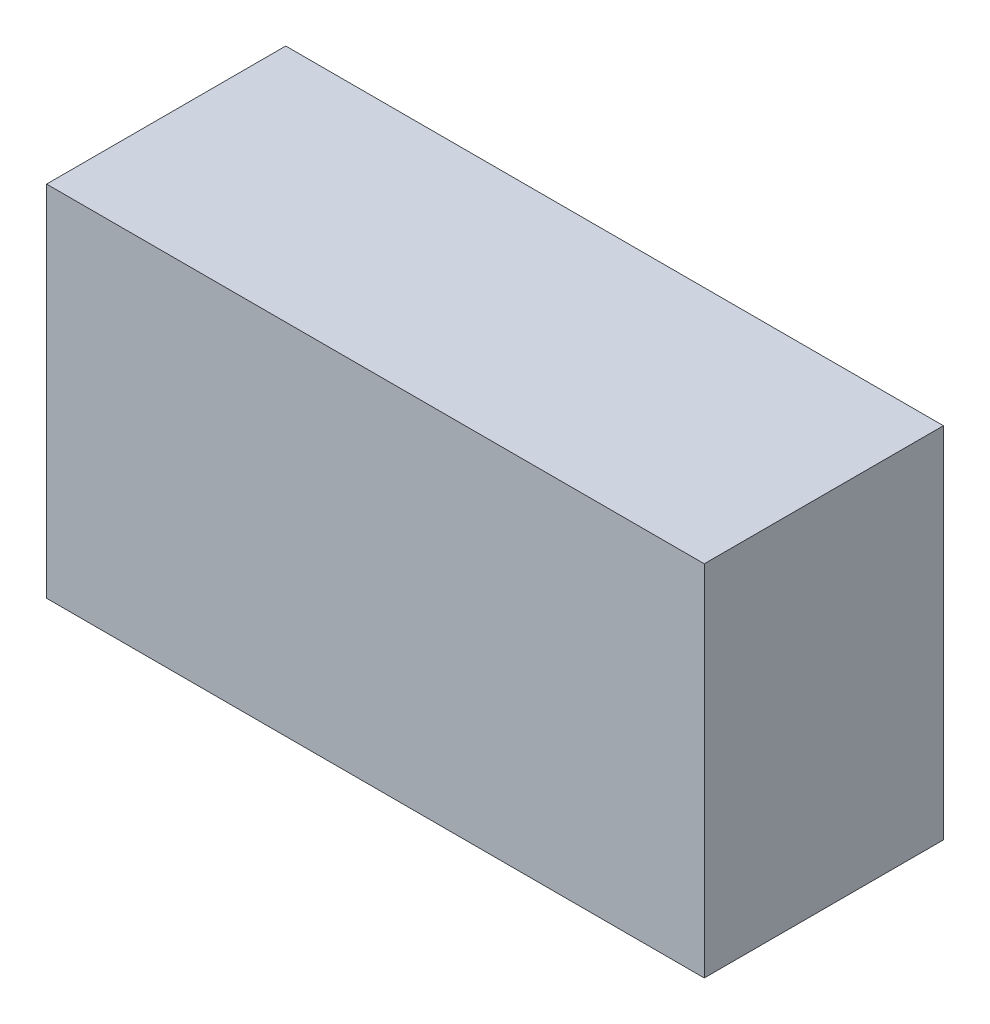
SolidWorks part; units mm, degrees
ref_plane "Спереди" through (0, 0, 0) normal (0, 0, 1) x (1, 0, 0)
ref_plane "Сверху" through (0, 0, 0) normal (0, 1, 0) x (1, 0, 0)
ref_plane "Справа" through (0, 0, 0) normal (1, 0, 0) x (0, 0, -1)
sketch "Эскиз1" plane through (0, 0, 0) normal (0, 0, 1) x (1, 0, 0)
  line L1 (0, 0) -> (33, 0)
  line L2 (0, 0) -> (0, 18)
  line L3 (0, 18) -> (33, 18)
  line L4 (33, 0) -> (33, 18)
  dimension "D1" = 33
  dimension "D2" = 18
extrude "Бобышка-Вытянуть1" add sketch "Эскиз1" along normal blind 12
sketch "Эскиз2" plane through (0, 0, 0) normal (-1, 0, 0) x (0, 0, 1)
  line L4 (2.7, 4.53) -> (3.3, 4.53)
  line L5 (4.58, 5.81) -> (4.58, 12.19)
  line L6 (3.3, 13.47) -> (2.7, 13.47)
  line L7 (1.42, 12.19) -> (1.42, 5.81)
  line L8 (12, 18) -> (0, 18) construction
  line L9 (4.58, 9) -> (1.42, 9) construction
  line L10 (0, 18) -> (0, 0) construction
  line L11 (3, 13.47) -> (3, 4.53) construction
  arc A4 (3.3, 4.53) -> (4.58, 5.81) centre (3.3, 5.81) ccw
  arc A5 (4.58, 12.19) -> (3.3, 13.47) centre (3.3, 12.19) ccw
  arc A6 (2.7, 13.47) -> (1.42, 12.19) centre (2.7, 12.19) ccw
  arc A7 (1.42, 5.81) -> (2.7, 4.53) centre (2.7, 5.81) ccw
  dimension "D2" = 1.28
  dimension "D4" = 1.28
  dimension "D6" = 1.28
  dimension "D8" = 1.28
  dimension "D1" = 6.38
  dimension "D3" = 0.6
  dimension "D5" = 6.38
  dimension "D7" = 0.6
  dimension "D9" = 8.94
  dimension "D10" = 9
  dimension "D11" = 0.6
  dimension "D12" = 0.6
  dimension "D13" = 8.9601
  dimension "D14" = 7.1197
  dimension "D15" = 3
extrude "Бобышка-Вытянуть2" add sketch "Эскиз2" along normal blind 2
sketch "Эскиз3" plane through (-2, 0, 0) normal (-1, 0, 0) x (0, 0, 1)
  line L4 (2.7, 4.53) -> (3.3, 4.53)
  line L5 (4.58, 5.81) -> (4.58, 12.19)
  line L6 (3.3, 13.47) -> (2.7, 13.47)
  line L7 (1.42, 12.19) -> (1.42, 5.81)
  line L8 (2.7, 4.53) -> (3.3, 4.53)
  line L9 (4.58, 5.81) -> (4.58, 12.19)
  line L10 (3.3, 13.47) -> (2.7, 13.47)
  line L11 (1.42, 12.19) -> (1.42, 5.81)
  line L12 (0, 18) -> (0, 0)
  line L13 (0, 0) -> (12, 0)
  line L14 (12, 0) -> (12, 18)
  line L15 (12, 18) -> (0, 18)
  line L16 (0, 18) -> (0, 0)
  line L17 (0, 0) -> (12, 0)
  line L18 (12, 0) -> (12, 18)
  line L19 (12, 18) -> (0, 18)
  arc A4 (1.42, 5.81) -> (2.7, 4.53) centre (2.7, 5.81) ccw
  arc A5 (3.3, 4.53) -> (4.58, 5.81) centre (3.3, 5.81) ccw
  arc A6 (4.58, 12.19) -> (3.3, 13.47) centre (3.3, 12.19) ccw
  arc A7 (2.7, 13.47) -> (1.42, 12.19) centre (2.7, 12.19) ccw
  arc A8 (1.42, 5.81) -> (2.7, 4.53) centre (2.7, 5.81) ccw
  arc A9 (3.3, 4.53) -> (4.58, 5.81) centre (3.3, 5.81) ccw
  arc A10 (4.58, 12.19) -> (3.3, 13.47) centre (3.3, 12.19) ccw
  arc A11 (2.7, 13.47) -> (1.42, 12.19) centre (2.7, 12.19) ccw
  dimension "D1" = 0
  dimension "D2" = 0
